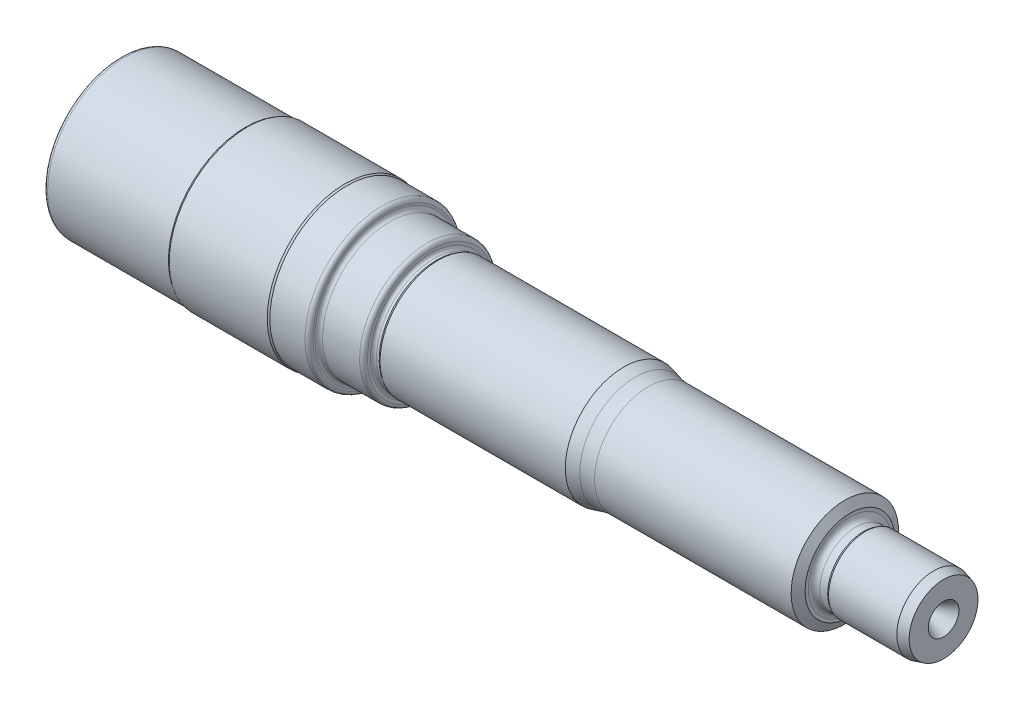
SolidWorks part; units mm, degrees
material "Plain Carbon Steel"
ref_plane "Front Plane" through (0, 0, 0) normal (0, 0, 1) x (1, 0, 0)
ref_plane "Top Plane" through (0, 0, 0) normal (0, 1, 0) x (1, 0, 0)
ref_plane "Right Plane" through (0, 0, 0) normal (1, 0, 0) x (0, 0, -1)
sketch "Sketch2" plane through (0, 0, 0) normal (0, 0, 1) x (1, 0, 0)
  line L0 (0, 15.866) -> (0, 18.75)
  line L1 (1, 19.75) -> (32, 19.75)
  line L2 (32, 19.75) -> (32.433, 20)
  line L3 (32.433, 20) -> (57.567, 20)
  line L4 (57.567, 20) -> (58, 19.75)
  line L5 (58, 19.75) -> (67, 19.75)
  line L6 (68, 18.75) -> (68, 18.25)
  line L7 (69, 17.25) -> (78.5, 17.25)
  line L8 (79.5, 16.25) -> (79.5, 15.5)
  line L9 (80.3, 14.7) -> (80.9804, 14.7)
  line L10 (80.9804, 14.7) -> (81.5, 15)
  line L11 (81.5, 15) -> (129, 15)
  line L12 (129, 15) -> (131.9186, 14.218)
  line L13 (135.2832, 13.775) -> (185.6865, 13.775)
  line L14 (185.6865, 13.775) -> (187, 11.5)
  line L15 (187, 11.5) -> (187, 10.7)
  line L16 (188.5, 9.2) -> (190.4804, 9.2)
  line L17 (190.4804, 9.2) -> (191, 9.5)
  line L18 (191, 9.5) -> (208.5, 9.5)
  line L19 (211, 8.8301) -> (211, 3.9368)
  line L20 (211, 3.9368) -> (206.9093, 1.575)
  line L21 (206.9093, 1.575) -> (204.9093, 1.575)
  line L22 (204.9093, 1.575) -> (204, 0)
  line L23 (204, 0) -> (63, 0)
  line L24 (63, 0) -> (63, 12.5)
  line L25 (61, 14.5) -> (55.299, 14.5)
  line L26 (55.299, 14.5) -> (50, 11.8)
  line L27 (50, 11.8) -> (7.2, 11.8)
  line L28 (7.2, 11.8) -> (4, 15)
  line L29 (4, 15) -> (1.5, 15)
  line L30 (1.5, 15) -> (0, 15.866)
  line L31 (208.5, 9.5) -> (211, 8.8301)
  arc A0 (0, 18.75) -> (1, 19.75) centre (1, 18.75) cw
  arc A1 (61, 14.5) -> (63, 12.5) centre (61, 12.5) cw
  arc A2 (79.5, 16.25) -> (78.5, 17.25) centre (78.5, 16.25) ccw
  arc A3 (69, 17.25) -> (68, 18.25) centre (69, 18.25) cw
  arc A4 (68, 18.75) -> (67, 19.75) centre (67, 18.75) ccw
  arc A5 (80.3, 14.7) -> (79.5, 15.5) centre (80.3, 15.5) cw
  arc A6 (188.5, 9.2) -> (187, 10.7) centre (188.5, 10.7) cw
  arc A7 (135.2832, 13.775) -> (131.9186, 14.218) centre (135.2832, 26.775) cw
  point P0 (0, 15)
  point P3 (211, 9.5)
  point P34 (0, 19.75)
  point P40 (79.5, 17.25)
  point P53 (133.5718, 13.775)
  dimension "D38" = 1
  dimension "D41" = 2
  dimension "D42" = 1
  dimension "D43" = 0.8
  dimension "D46" = 1.5
  dimension "D47" = 13
  dimension "D1" = 211
  dimension "D2" = 32
  dimension "D3" = 68
  dimension "D4" = 26
  dimension "D5" = 30
  dimension "D6" = 19.75
  dimension "D7" = 20
  dimension "D8" = 79.5
  dimension "D9" = 81.5
  dimension "D10" = 1.5
  dimension "D11" = 11.8
  dimension "D12" = 14.5
  dimension "D13" = 63
  dimension "D14" = 50
  dimension "D15" = 27
  dimension "D16" = 45
  dimension "D17" = 4
  dimension "D18" = 129
  dimension "D19" = 187
  dimension "D20" = 4
  dimension "D21" = 7
  dimension "D22" = 60
  dimension "D23" = 2
  dimension "D24" = 1.575
  dimension "D25" = 30
  dimension "D26" = 9.5
  dimension "D27" = 9.2
  dimension "D28" = 30
  dimension "D29" = 11.5
  dimension "D30" = 13.775
  dimension "D31" = 30
  dimension "D32" = 14.7
  dimension "D33" = 15
  dimension "D34" = 15
  dimension "D35" = 17.25
  dimension "D36" = 19.75
  dimension "D37" = 30
  dimension "D39" = 30
  dimension "D40" = 15
  dimension "D44" = 2.5
  dimension "D45" = 15
revolve "Revolve1" add sketch "Sketch2" angle 360 about L23
sketch "Sketch3" plane through (211, 0, 0) normal (1, 0, 0) x (0, 0, -1)
  line L0 (0, 0) -> (-1.5655, 11.8974) construction
  arc A0 (-2.5627, 13.5345) -> (-7.7568, 11.3835) centre (0, 0) ccw construction
  arc A1 (3.1074, 11.5907) -> (0, 12) centre (0, 0) ccw
  arc A2 (-3.1043, 11.5915) -> (-6, 10.3923) centre (0, 0) ccw construction
  arc A3 (4.5479, 13.0026) -> (-1.0258, 13.7367) centre (0, 0) ccw
  arc A4 (8.4864, 8.4842) -> (6, 10.3923) centre (0, 0) ccw construction
  arc A5 (10.4399, 8.9866) -> (5.98, 12.4093) centre (0, 0) ccw construction
  arc A6 (11.5915, 3.1043) -> (10.3923, 6) centre (0, 0) ccw construction
  arc A7 (13.5345, 2.5627) -> (11.3835, 7.7568) centre (0, 0) ccw construction
  arc A8 (11.5907, -3.1074) -> (12, 0) centre (0, 0) ccw construction
  arc A9 (13.0026, -4.5479) -> (13.7367, 1.0258) centre (0, 0) ccw construction
  arc A10 (8.9866, -10.4399) -> (12.4093, -5.98) centre (0, 0) ccw construction
  arc A11 (8.4842, -8.4864) -> (10.3923, -6) centre (0, 0) ccw construction
  arc A12 (3.1043, -11.5915) -> (6, -10.3923) centre (0, 0) ccw construction
  arc A13 (-4.5479, -13.0026) -> (7.7568, -11.3835) centre (0, 0) ccw construction
  arc A14 (-3.1074, -11.5907) -> (0, -12) centre (0, 0) ccw construction
  arc A15 (-8.4864, -8.4842) -> (-6, -10.3923) centre (0, 0) ccw construction
  arc A16 (-10.4399, -8.9866) -> (-5.98, -12.4093) centre (0, 0) ccw construction
  arc A17 (-11.5915, -3.1043) -> (-10.3923, -6) centre (0, 0) ccw construction
  arc A18 (-13.5345, -2.5627) -> (-11.3835, -7.7568) centre (0, 0) ccw construction
  arc A19 (-11.5907, 3.1074) -> (-12, 0) centre (0, 0) ccw construction
  arc A20 (-13.0026, 4.5479) -> (-13.7367, -1.0258) centre (0, 0) ccw construction
  arc A21 (-8.4842, 8.4864) -> (-10.3923, 6) centre (0, 0) ccw construction
  arc A22 (-8.9866, 10.4399) -> (-12.4093, 5.98) centre (0, 0) ccw construction
  spline S0 degree 3 poles (0, 12) (-0.0366, 12.1032) (-0.1224, 12.3264) (-0.2974, 12.6733) (-0.5245, 13.0595) (-0.7734, 13.4188) (-0.9508, 13.6452) (-1.0258, 13.7367) knots 0.250165 0.250165 0.250165 0.250165 0.360158 0.490165 0.640141 0.810086 0.928975 0.928975 0.928975 0.928975
  spline S1 degree 3 poles (-3.1043, 11.5915) (-3.0956, 11.7007) (-3.0705, 11.9384) (-2.9912, 12.3189) (-2.8717, 12.7507) (-2.7242, 13.1621) (-2.6114, 13.4267) (-2.5627, 13.5345) knots 0.250165 0.250165 0.250165 0.250165 0.360158 0.490165 0.640141 0.810086 0.928975 0.928975 0.928975 0.928975 construction
  spline S2 degree 3 poles (3.1074, 11.5907) (3.1695, 11.6809) (3.3101, 11.8742) (3.569, 12.164) (3.8883, 12.4783) (4.2218, 12.7608) (4.4518, 12.9336) (4.5479, 13.0026) knots 0.250165 0.250165 0.250165 0.250165 0.360158 0.490165 0.640141 0.810086 0.928975 0.928975 0.928975 0.928975
  spline S3 degree 3 poles (6, 10.3923) (6.0199, 10.5) (6.0572, 10.7361) (6.0791, 11.1241) (6.0755, 11.5721) (6.0396, 12.0077) (5.9991, 12.2925) (5.98, 12.4093) knots 0.250165 0.250165 0.250165 0.250165 0.360158 0.490165 0.640141 0.810086 0.928975 0.928975 0.928975 0.928975 construction
  spline S4 degree 3 poles (8.4864, 8.4842) (8.5853, 8.5312) (8.8037, 8.6283) (9.1729, 8.7499) (9.6065, 8.8623) (10.0366, 8.9403) (10.3222, 8.9749) (10.4399, 8.9866) knots 0.250165 0.250165 0.250165 0.250165 0.360158 0.490165 0.640141 0.810086 0.928975 0.928975 0.928975 0.928975 construction
  spline S5 degree 3 poles (10.3923, 6) (10.4633, 6.0833) (10.6138, 6.2692) (10.8267, 6.5942) (11.0476, 6.984) (11.2343, 7.3792) (11.3417, 7.6461) (11.3835, 7.7568) knots 0.250165 0.250165 0.250165 0.250165 0.360158 0.490165 0.640141 0.810086 0.928975 0.928975 0.928975 0.928975 construction
  spline S6 degree 3 poles (11.5915, 3.1043) (11.7007, 3.0956) (11.9384, 3.0705) (12.3189, 2.9912) (12.7507, 2.8717) (13.1621, 2.7242) (13.4267, 2.6114) (13.5345, 2.5627) knots 0.250165 0.250165 0.250165 0.250165 0.360158 0.490165 0.640141 0.810086 0.928975 0.928975 0.928975 0.928975 construction
  spline S7 degree 3 poles (12, 0) (12.1032, 0.0366) (12.3264, 0.1224) (12.6733, 0.2974) (13.0595, 0.5245) (13.4188, 0.7734) (13.6452, 0.9508) (13.7367, 1.0258) knots 0.250165 0.250165 0.250165 0.250165 0.360158 0.490165 0.640141 0.810086 0.928975 0.928975 0.928975 0.928975 construction
  spline S8 degree 3 poles (11.5907, -3.1074) (11.6809, -3.1695) (11.8742, -3.3101) (12.164, -3.569) (12.4783, -3.8883) (12.7608, -4.2218) (12.9336, -4.4518) (13.0026, -4.5479) knots 0.250165 0.250165 0.250165 0.250165 0.360158 0.490165 0.640141 0.810086 0.928975 0.928975 0.928975 0.928975 construction
  spline S9 degree 3 poles (10.3923, -6) (10.5, -6.0199) (10.7361, -6.0572) (11.1241, -6.0791) (11.5721, -6.0755) (12.0077, -6.0396) (12.2925, -5.9991) (12.4093, -5.98) knots 0.250165 0.250165 0.250165 0.250165 0.360158 0.490165 0.640141 0.810086 0.928975 0.928975 0.928975 0.928975 construction
  spline S10 degree 3 poles (8.4842, -8.4864) (8.5312, -8.5853) (8.6283, -8.8037) (8.7499, -9.1729) (8.8623, -9.6065) (8.9403, -10.0366) (8.9749, -10.3222) (8.9866, -10.4399) knots 0.250165 0.250165 0.250165 0.250165 0.360158 0.490165 0.640141 0.810086 0.928975 0.928975 0.928975 0.928975 construction
  spline S11 degree 3 poles (6, -10.3923) (6.0833, -10.4633) (6.2692, -10.6138) (6.5942, -10.8267) (6.984, -11.0476) (7.3792, -11.2343) (7.6461, -11.3417) (7.7568, -11.3835) knots 0.250165 0.250165 0.250165 0.250165 0.360158 0.490165 0.640141 0.810086 0.928975 0.928975 0.928975 0.928975 construction
  spline S12 degree 3 poles (3.1043, -11.5915) (3.0956, -11.7007) (3.0705, -11.9384) (2.9912, -12.3189) (2.8717, -12.7507) (2.7242, -13.1621) (2.6114, -13.4267) (2.5627, -13.5345) knots 0.250165 0.250165 0.250165 0.250165 0.360158 0.490165 0.640141 0.810086 0.928975 0.928975 0.928975 0.928975 construction
  spline S13 degree 3 poles (0, -12) (0.0366, -12.1032) (0.1224, -12.3264) (0.2974, -12.6733) (0.5245, -13.0595) (0.7734, -13.4188) (0.9508, -13.6452) (1.0258, -13.7367) knots 0.250165 0.250165 0.250165 0.250165 0.360158 0.490165 0.640141 0.810086 0.928975 0.928975 0.928975 0.928975 construction
  spline S14 degree 3 poles (-3.1074, -11.5907) (-3.1695, -11.6809) (-3.3101, -11.8742) (-3.569, -12.164) (-3.8883, -12.4783) (-4.2218, -12.7608) (-4.4518, -12.9336) (-4.5479, -13.0026) knots 0.250165 0.250165 0.250165 0.250165 0.360158 0.490165 0.640141 0.810086 0.928975 0.928975 0.928975 0.928975 construction
  spline S15 degree 3 poles (-6, -10.3923) (-6.0199, -10.5) (-6.0572, -10.7361) (-6.0791, -11.1241) (-6.0755, -11.5721) (-6.0396, -12.0077) (-5.9991, -12.2925) (-5.98, -12.4093) knots 0.250165 0.250165 0.250165 0.250165 0.360158 0.490165 0.640141 0.810086 0.928975 0.928975 0.928975 0.928975 construction
  spline S16 degree 3 poles (-8.4864, -8.4842) (-8.5853, -8.5312) (-8.8037, -8.6283) (-9.1729, -8.7499) (-9.6065, -8.8623) (-10.0366, -8.9403) (-10.3222, -8.9749) (-10.4399, -8.9866) knots 0.250165 0.250165 0.250165 0.250165 0.360158 0.490165 0.640141 0.810086 0.928975 0.928975 0.928975 0.928975 construction
  spline S17 degree 3 poles (-10.3923, -6) (-10.4633, -6.0833) (-10.6138, -6.2692) (-10.8267, -6.5942) (-11.0476, -6.984) (-11.2343, -7.3792) (-11.3417, -7.6461) (-11.3835, -7.7568) knots 0.250165 0.250165 0.250165 0.250165 0.360158 0.490165 0.640141 0.810086 0.928975 0.928975 0.928975 0.928975 construction
  spline S18 degree 3 poles (-11.5915, -3.1043) (-11.7007, -3.0956) (-11.9384, -3.0705) (-12.3189, -2.9912) (-12.7507, -2.8717) (-13.1621, -2.7242) (-13.4267, -2.6114) (-13.5345, -2.5627) knots 0.250165 0.250165 0.250165 0.250165 0.360158 0.490165 0.640141 0.810086 0.928975 0.928975 0.928975 0.928975 construction
  spline S19 degree 3 poles (-12, 0) (-12.1032, -0.0366) (-12.3264, -0.1224) (-12.6733, -0.2974) (-13.0595, -0.5245) (-13.4188, -0.7734) (-13.6452, -0.9508) (-13.7367, -1.0258) knots 0.250165 0.250165 0.250165 0.250165 0.360158 0.490165 0.640141 0.810086 0.928975 0.928975 0.928975 0.928975 construction
  spline S20 degree 3 poles (-11.5907, 3.1074) (-11.6809, 3.1695) (-11.8742, 3.3101) (-12.164, 3.569) (-12.4783, 3.8883) (-12.7608, 4.2218) (-12.9336, 4.4518) (-13.0026, 4.5479) knots 0.250165 0.250165 0.250165 0.250165 0.360158 0.490165 0.640141 0.810086 0.928975 0.928975 0.928975 0.928975 construction
  spline S21 degree 3 poles (-10.3923, 6) (-10.5, 6.0199) (-10.7361, 6.0572) (-11.1241, 6.0791) (-11.5721, 6.0755) (-12.0077, 6.0396) (-12.2925, 5.9991) (-12.4093, 5.98) knots 0.250165 0.250165 0.250165 0.250165 0.360158 0.490165 0.640141 0.810086 0.928975 0.928975 0.928975 0.928975 construction
  spline S22 degree 3 poles (-8.4842, 8.4864) (-8.5312, 8.5853) (-8.6283, 8.8037) (-8.7499, 9.1729) (-8.8623, 9.6065) (-8.9403, 10.0366) (-8.9749, 10.3222) (-8.9866, 10.4399) knots 0.250165 0.250165 0.250165 0.250165 0.360158 0.490165 0.640141 0.810086 0.928975 0.928975 0.928975 0.928975 construction
  spline S23 degree 3 poles (-6, 10.3923) (-6.0833, 10.4633) (-6.2692, 10.6138) (-6.5942, 10.8267) (-6.984, 11.0476) (-7.3792, 11.2343) (-7.6461, 11.3417) (-7.7568, 11.3835) knots 0.250165 0.250165 0.250165 0.250165 0.360158 0.490165 0.640141 0.810086 0.928975 0.928975 0.928975 0.928975 construction
  point P146 (0, 0)
sketch "Sketch5" plane through (0, 0, 0) normal (0, 0, 1) x (1, 0, 0)
  line L0 (0, 0) -> (211, 0) construction
  line L1 (141, 12) -> (211, 12)
  arc A0 (132, 13.775) -> (141, 12) centre (141, 35.7044) ccw
sweep "Cut-Sweep1" [suppressed] cut profiles "Sketch3" path "Sketch5"
pattern_circular "CirPattern1" [suppressed] count 12 over 360
ref_plane "Plane1" through (4, 0, 0) normal (1, 0, 0) x (0, 0, -1)
sketch "Sketch6" plane through (4, 0, 0) normal (1, 0, 0) x (0, 0, -1)
  line L0 (-1.6, 9.6188) -> (-1.6, 11.691) construction
  line L1 (-0.8, 13.7768) -> (-0.8, 15.0672) construction
  line L2 (0, 22) -> (0, -22) construction
  arc A0 (-1.6, 11.691) -> (1.6, 11.691) centre (0, 0) ccw
  arc A1 (0.8, 13.7768) -> (-0.8, 13.7768) centre (0, 0) ccw
  arc A3 (-0.8, 13.7768) -> (-1.6, 11.691) centre (4.5574, 10.5257) ccw
  arc A4 (0.8, 13.7768) -> (1.6, 11.691) centre (-4.5574, 10.5257) cw
  dimension "D1" = 23.6
  dimension "D2" = 27.6
  dimension "D3" = 1.6
  dimension "D4" = 0.8
extrude "Cut-Extrude1" [suppressed] cut sketch "Sketch6" along normal up to next
pattern_circular "CirPattern2" [suppressed] count 12 over 360
